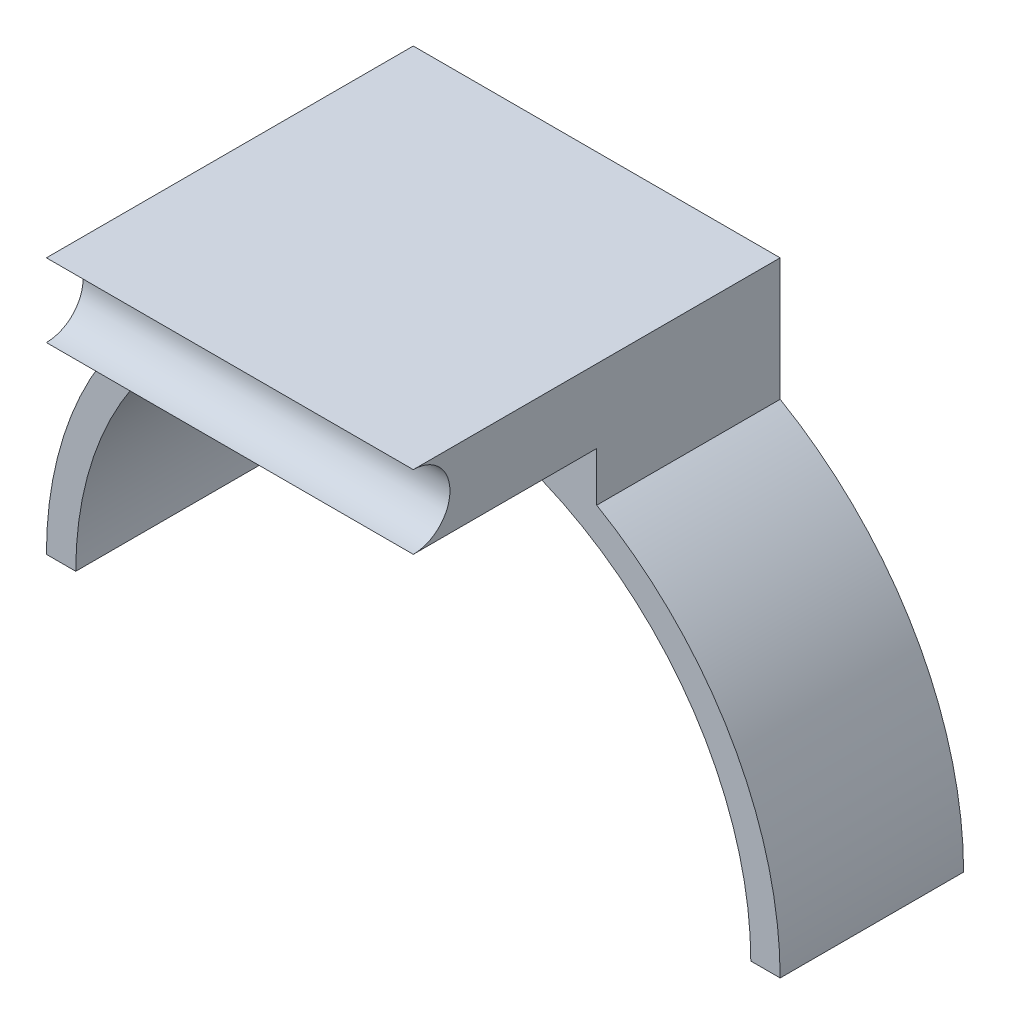
SolidWorks part; units mm, degrees
ref_plane "Front" through (0, 0, 0) normal (0, 0, 1) x (1, 0, 0)
ref_plane "Top" through (0, 0, 0) normal (0, 1, 0) x (1, 0, 0)
ref_plane "Right" through (0, 0, 0) normal (1, 0, 0) x (0, 0, -1)
sketch "草图1" plane through (0, 0, 0) normal (0, 0, 1) x (1, 0, 0)
  line L0 (-23.0866, 0) -> (0, 0) construction
  line L1 (0, 0) -> (0, 28.5445) construction
  line L3 (-25, 5) -> (25, 5)
  line L4 (-25, 5) -> (-25, -5)
  line L5 (-25, -5) -> (25, -5)
  line L6 (25, 5) -> (25, -5)
  dimension "D1" = 50
  dimension "D2" = 10
  dimension "D3" = 5
  dimension "D4" = 25
extrude "凸台-拉伸1" add sketch "草图1" along normal blind 50
sketch "草图4" plane through (0, 0, 0) normal (0, 0, -1) x (-1, 0, 0)
  line L0 (0, -5) -> (0, -37.0421) construction
  line L1 (25, -5) -> (-25, -5) construction
  line L2 (-25, -5) -> (25, -5)
  line L3 (25, -5) -> (25, -11.6987)
  line L4 (-25, -5) -> (-25, -11.6987)
  line L5 (46, -55) -> (50, -55)
  line L6 (-46, -55) -> (-50, -55)
  arc A0 (-25, -11.6987) -> (-50, -55) centre (0, -55) ccw
  arc A1 (46, -55) -> (-46, -55) centre (0, -55) ccw
  arc A2 (50, -55) -> (25, -11.6987) centre (0, -55) ccw
extrude "凸台-拉伸3" add sketch "草图4" against normal blind 25
sketch "草图5" plane through (25, 0, 0) normal (1, 0, 0) x (0, 0, -1)
  line L0 (-50, 0) -> (-38.648, 0) construction
  line L1 (-50, -5) -> (-50, 5) construction
  circle A0 centre (-50, 0) radius 5
extrude "切除-拉伸2" cut sketch "草图5" against normal through all
